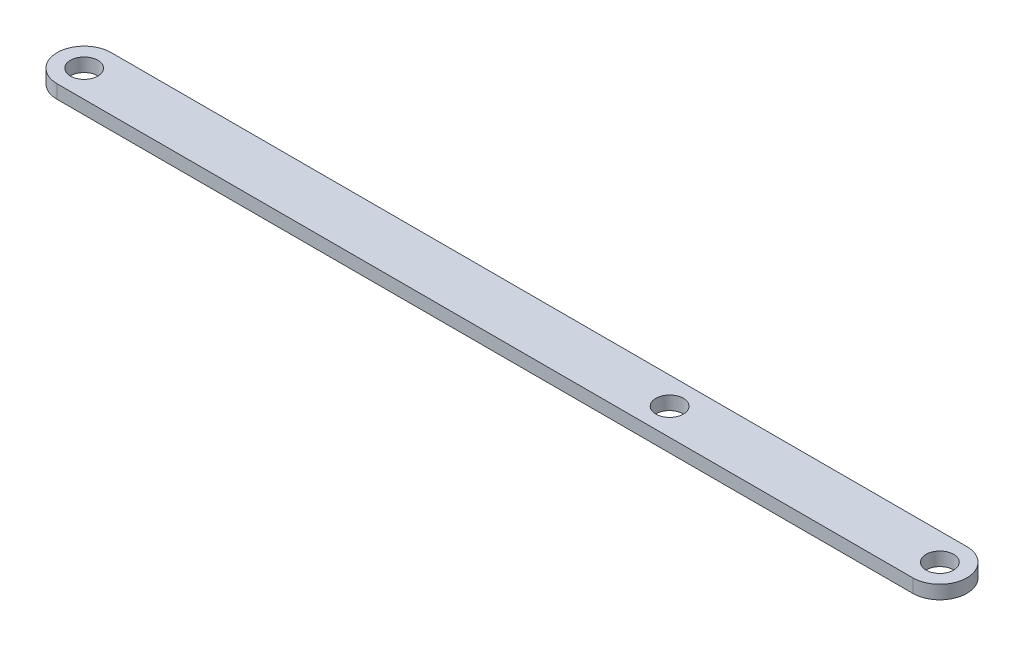
SolidWorks part; units mm, degrees
material "ABS"
ref_plane "Front Plane" through (0, 0, 0) normal (0, 0, 1) x (1, 0, 0)
ref_plane "Top Plane" through (0, 0, 0) normal (0, 1, 0) x (1, 0, 0)
ref_plane "Right Plane" through (0, 0, 0) normal (1, 0, 0) x (0, 0, -1)
sketch "Sketch1" plane through (0, 0, 0) normal (0, 1, 0) x (1, 0, 0)
  line L0 (0, 0) -> (190, 0) construction
  line L1 (0, 6) -> (190, 6)
  line L2 (0, -6) -> (190, -6)
  arc A0 (0, 6) -> (0, -6) centre (0, 0) ccw
  arc A1 (190, -6) -> (190, 6) centre (190, 0) ccw
  circle A2 centre (0, 0) radius 3.05
  circle A3 centre (130, 0) radius 3.05
  circle A4 centre (190, 0) radius 3.05
  point P3 (95, 0)
  dimension "D3" = 6.1
  dimension "D4" = 60
  dimension "D1" = 190
  dimension "D2" = 12
extrude "Boss-Extrude1" add sketch "Sketch1" along normal blind 3
